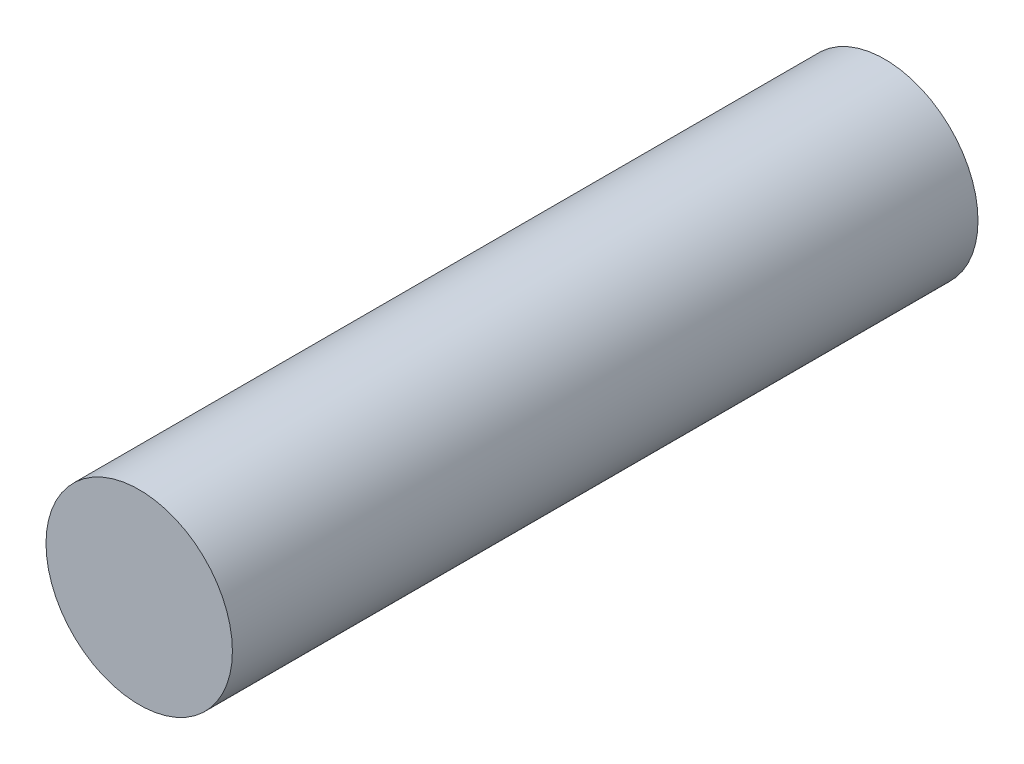
SolidWorks part; units mm, degrees
ref_plane "Front Plane" through (0, 0, 0) normal (0, 0, 1) x (1, 0, 0)
ref_plane "Top Plane" through (0, 0, 0) normal (0, 1, 0) x (1, 0, 0)
ref_plane "Right Plane" through (0, 0, 0) normal (1, 0, 0) x (0, 0, -1)
sketch "Sketch1" plane through (0, 0, 0) normal (0, 0, 1) x (1, 0, 0)
  circle A1 centre (-3.25, -0.25) radius 1.5
  circle A2 centre (-3.25, -0.25) radius 1.5
  dimension "D1" = 0
extrude "Boss-Extrude1" add sketch "Sketch1" along normal blind 12
